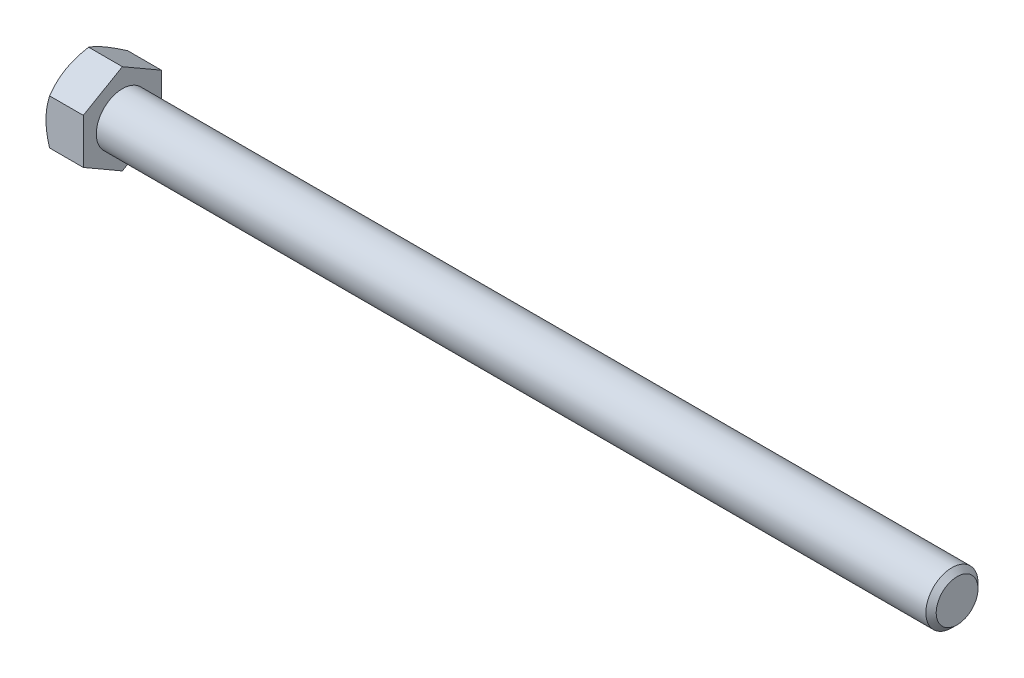
SolidWorks part; units mm, degrees
ref_plane "Plane1" through (0, 0, 0) normal (0, 0, 1) x (1, 0, 0)
ref_plane "Plane2" through (0, 0, 0) normal (0, 1, 0) x (1, 0, 0)
ref_plane "Plane3" through (0, 0, 0) normal (1, 0, 0) x (0, 0, -1)
sketch "Sketch1" plane through (0, 0, 0) normal (1, 0, 0) x (0, 0, -1)
  line L0 (7.1374, 4.1208) -> (7.1374, -4.1208)
  line L1 (-7.1374, 4.1208) -> (-7.1374, -4.1208)
  line L2 (7.1374, -4.1208) -> (0, -8.2416)
  line L3 (0, -8.2416) -> (-7.1374, -4.1208)
  line L4 (7.1374, 4.1208) -> (0, 8.2416)
  line L5 (0, 8.2416) -> (-7.1374, 4.1208)
  dimension "Width_flats" = 14.2748
  dimension "D2" = 120
  dimension "D3" = 7.1374
  dimension "D4" = 7.1374
  dimension "D5" = 7.1374
extrude "BaseHead" add sketch "Sketch1" along normal blind 6.8072
sketch "BodySke" plane through (0, 0, 0) normal (0, 0, 1) x (1, 0, 0)
  line L0 (0, 4.1208) -> (0, -4.1208) construction
  line L1 (0, 0) -> (159.2072, 0)
  line L2 (0, 0) -> (0, 4.7625)
  line L3 (0, 4.7625) -> (158.2611, 4.7625)
  line L4 (159.2072, 0) -> (159.2072, 3.8163)
  line L5 (6.8072, 8.2416) -> (6.8072, 4.1208) construction
  line L6 (159.2072, 3.8163) -> (158.2611, 4.7625)
  line L7 (0, 0) -> (96.52, 0) construction
  line L8 (159.2072, -3.8163) -> (158.2611, -4.7625) construction
  line L9 (0, -4.7625) -> (158.2611, -4.7625) construction
  line L10 (8.3947, 15.24) -> (8.3947, -2.54) construction
  line L11 (133.8072, 15.24) -> (133.8072, -2.54) construction
  line L12 (6.8072, 4.1208) -> (6.8072, -4.1208) construction
  dimension "Length" = 152.4
  dimension "Body_ch_ang" = 45
  dimension "Diameter" = 9.525
  dimension "Minor_dia" = 7.6327
  dimension "Advance" = 1.5875
  dimension "Thread_nom" = 25.4
revolve "BaseBody" add sketch "BodySke" angle 360 about L7
cosmetic thread "ThreadCosmetic" [suppressed] parameters "Thread_length"=25.4, "Thread_minor"=7.6327
sketch "Sketch3" plane through (0, 0, 0) normal (0, 0, 1) x (1, 0, 0)
  line L0 (0, 7.1374) -> (4.3037, 14.5916)
  line L1 (0, 8.2416) -> (0, 4.1208) construction
  line L2 (4.3037, 14.5916) -> (4.3037, 20.9416)
  line L3 (4.3037, 20.9416) -> (-12.7, 20.9416)
  line L4 (-12.7, 20.9416) -> (-12.7, 7.1374)
  line L5 (-12.7, 7.1374) -> (0, 7.1374)
  line L6 (0, 0) -> (99.06, 0) construction
  line L7 (6.8072, 8.2416) -> (0, 8.2416) construction
  dimension "D1" = 7.1374
  dimension "D2" = 6.35
  dimension "D3" = 12.7
  dimension "D4" = 6.35
  dimension "Head_ch_ang" = 30
revolve "HeadChamfer" cut sketch "Sketch3" angle 360 about L6
fillet "HeadFillet" [suppressed] radius 0.762
sketch "ThdSchSke" plane through (0, 0, 0) normal (0, 0, 1) x (1, 0, 0)
  line L0 (133.8072, -3.8163) -> (133.1447, -4.7625)
  line L1 (133.8072, -3.8163) -> (134.4697, -4.7625)
  line L2 (134.4697, -4.7625) -> (134.4697, -5.9531)
  line L3 (-3.175, 0) -> (5.1513, 0) construction
  line L5 (134.4697, -5.9531) -> (133.1447, -5.9531)
  line L6 (133.1447, -5.9531) -> (133.1447, -4.7625)
  dimension "Thread_minor" = 7.6327
  dimension "Diameter" = 9.525
  dimension "Start" = 133.8072
  dimension "SideAngle" = 55
  dimension "VeeAngle" = 70
  dimension "Overcut" = 11.9063
revolve "ThreadSchematic" [suppressed] cut sketch "ThdSchSke" angle 360 about L3
pattern_linear "ThdSchPat" [suppressed]
equation "\"D3@Sketch1\" = \"Width_flats@Sketch1\" / 2"
equation "\"D4@Sketch1\" = \"D3@Sketch1\""
equation "\"D5@Sketch1\" = \"D4@Sketch1\""
equation "\"Thread_minor@ThreadCosmetic\" = \"Minor_dia@BodySke\""
equation "\"D1@Sketch3\" = \"Width_flats@Sketch1\" / 2"
equation "\"Thread_length@ThreadCosmetic\" = ((sgn( (\"Length@BodySke\" - \"Advance@BodySke\" ) - \"Thread_nom@BodySke\" )-1)*( (\"Length@BodySke\" - \"Advance@BodySke\" ) - \"Thread_nom@BodySke\" ))/-2+ \"Thread_nom@BodySke\""
equation "\"Thread_minor@ThdSchSke\" = \"Minor_dia@BodySke\""
equation "\"Diameter@ThdSchSke\" = \"Diameter@BodySke\""
equation "\"Overcut@ThdSchSke\" = \"Diameter@BodySke\" * 1.25"
equation "\"Start@ThdSchSke\" = \"Head_ht@BaseHead\" + \"Length@BodySke\" - \"Thread_length@ThreadCosmetic\"  '---Non-countersunk---"
equation "\"Num_threads@ThdSchPat\" = int( \"Thread_length@ThreadCosmetic\" / \"Advance@BodySke\" + 0.999 )  + 1"
equation "\"Advance@ThdSchPat\" = \"Thread_length@ThreadCosmetic\" /  (\"Num_threads@ThdSchPat\" - 1) 'relax it"
equation "\"Num_threads@ThdSchPat\" = \"Num_threads@ThdSchPat\" - sgn( \"Num_threads@ThdSchPat\" - 1) '---chamfered tips only---"
